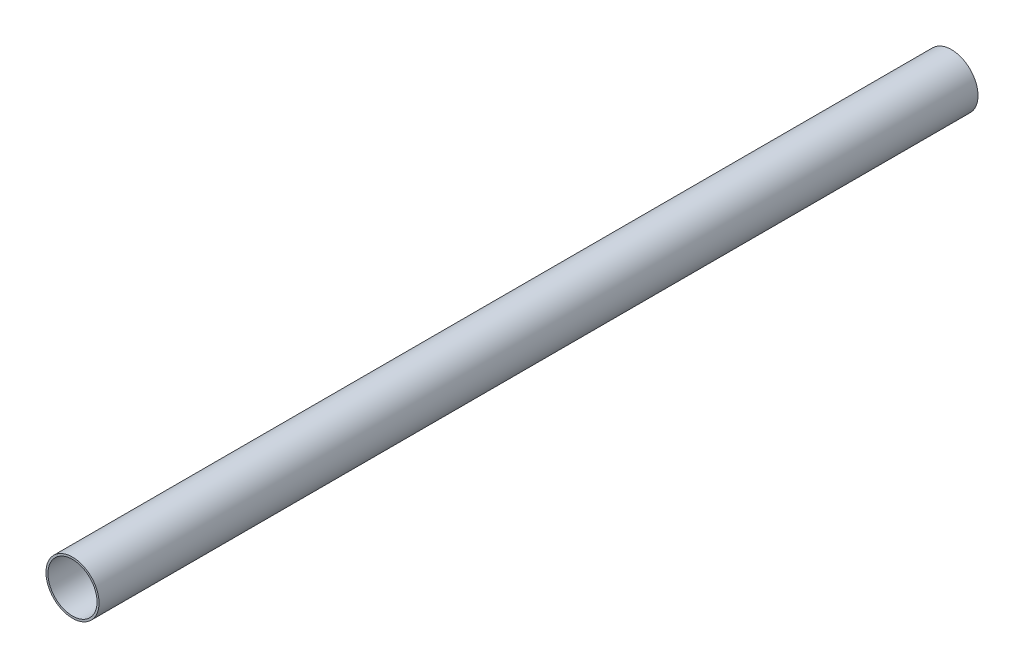
SolidWorks part; units mm, degrees
ref_plane "Front Plane" through (0, 0, 0) normal (0, 0, 1) x (1, 0, 0)
ref_plane "Top Plane" through (0, 0, 0) normal (0, 1, 0) x (1, 0, 0)
ref_plane "Right Plane" through (0, 0, 0) normal (1, 0, 0) x (0, 0, -1)
sketch "Sketch1" plane through (0, 0, 0) normal (0, 0, 1) x (1, 0, 0)
  circle A0 centre (0, 0) radius 8
  circle A1 centre (0, 0) radius 7.4
  dimension "D1" = 16
  dimension "D2" = 0.6
extrude "Boss-Extrude1" add sketch "Sketch1" along normal blind 265
